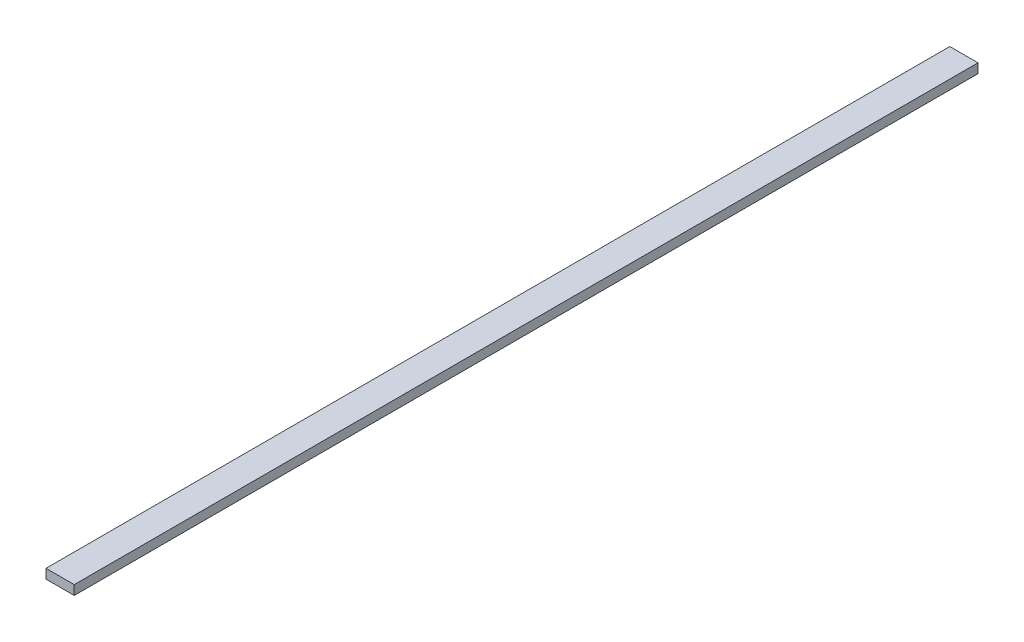
SolidWorks part; units mm, degrees
material "Pine"
ref_plane "Front Plane" through (0, 0, 0) normal (0, 0, 1) x (1, 0, 0)
ref_plane "Top Plane" through (0, 0, 0) normal (0, 1, 0) x (1, 0, 0)
ref_plane "Right Plane" through (0, 0, 0) normal (1, 0, 0) x (0, 0, -1)
sketch "Sketch1" plane through (0, 0, 0) normal (0, 0, 1) x (1, 0, 0)
  line L1 (0, 0) -> (38.1, 0)
  line L2 (0, 0) -> (0, 12.7)
  line L3 (0, 12.7) -> (38.1, 12.7)
  line L4 (38.1, 0) -> (38.1, 12.7)
  dimension "D1" = 38.1
  dimension "D2" = 12.7
extrude "Boss-Extrude1" add sketch "Sketch1" along normal blind 1219.2
sketch "Sketch2" plane through (0, 0, 0) normal (0, 0, -1) x (-1, 0, 0)
  line L1 (-38.1, 0) -> (-38.1, 12.7) construction
  line L2 (0, 12.7) -> (0, 0) construction
  line L3 (-19.05, 6.35) -> (-38.1, 6.35) construction
  line L4 (-19.05, 6.35) -> (0, 6.35) construction
  circle A0 centre (-28.575, 6.35) radius 0.8763
  circle A1 centre (-9.525, 6.35) radius 0.8763
  dimension "D1" = 1.7526
sketch "Sketch3" plane through (0, 0, 0) normal (0, -1, 0) x (1, 0, 0)
  line L0 (19.05, 1219.2) -> (19.05, 1174.75) construction
  line L1 (0, 1219.2) -> (38.1, 1219.2) construction
  line L2 (19.05, 1174.75) -> (19.05, 1130.3) construction
  line L3 (38.1, 609.6) -> (0, 609.6) construction
  line L4 (38.1, 1219.2) -> (38.1, 0) construction
  line L5 (0, 1219.2) -> (0, 0) construction
  line L6 (19.05, 609.6) -> (19.05, 654.05) construction
  line L7 (19.05, 609.6) -> (19.05, 565.15) construction
  circle A0 centre (19.05, 1196.975) radius 0.8763
  circle A1 centre (19.05, 1152.525) radius 0.8763
  circle A2 centre (19.05, 22.225) radius 0.8763
  circle A3 centre (19.05, 66.675) radius 0.8763
  circle A4 centre (19.05, 587.375) radius 0.8763
  circle A5 centre (19.05, 631.825) radius 0.8763
  dimension "D2" = 1.7526
  dimension "D4" = 1.7526
  dimension "D1" = 88.9
  dimension "D3" = 88.9
equation "\"length\"= 20"
equation "\"length\"= 22"
equation "\"length\"= 36"
equation "\"length\"= 26"
equation "\"length\"= 27"
equation "\"length\"= 28"
equation "\"length\"= 39"
equation "\"length\"= 96"
equation "\"length\"= 30"
equation "\"length\"= 32"
